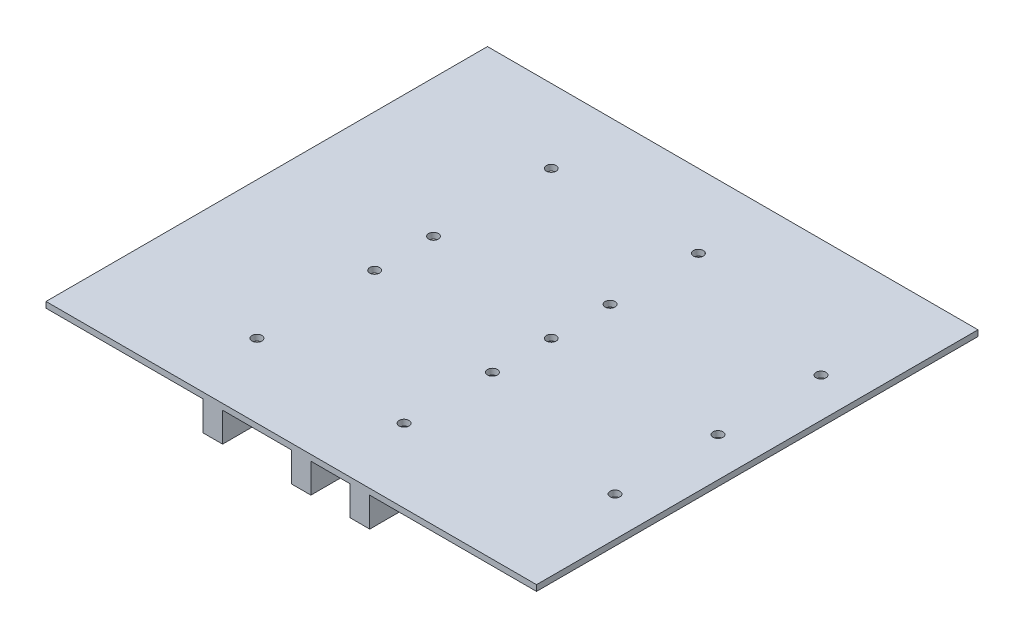
SolidWorks part; units mm, degrees
material "CA"
ref_plane "Front Plane" through (0, 0, 0) normal (0, 0, 1) x (1, 0, 0)
ref_plane "Top Plane" through (0, 0, 0) normal (0, 1, 0) x (1, 0, 0)
ref_plane "Right Plane" through (0, 0, 0) normal (1, 0, 0) x (0, 0, -1)
sketch "Sketch1" plane through (0, 0, 0) normal (0, 1, 0) x (1, 0, 0)
  line L1 (-250, 225) -> (250, 225)
  line L2 (-250, 225) -> (-250, -225)
  line L3 (-250, -225) -> (250, -225)
  line L4 (250, 225) -> (250, -225)
  line L5 (-250, 225) -> (250, -225) construction
  line L6 (-250, -225) -> (250, 225) construction
  point P0 (0, 0)
  dimension "D1" = 450
  dimension "D2" = 500
extrude "Boss-Extrude1" add sketch "Sketch1" along normal blind 6
sketch "Sketch2" plane through (0, 6, 0) normal (0, 1, 0) x (1, 0, 0)
  line L0 (40, 150) -> (40, -150) construction
  line L1 (210, 105) -> (210, -105) construction
  line L2 (0, 0) -> (210, 0) construction
  line L3 (-110, 150) -> (-110, -150) construction
  line L4 (40, 150) -> (-110, 150) construction
  line L5 (40, 0) -> (0, 0) construction
  line L7 (-110, 0) -> (0, 0) construction
  circle A0 centre (210, 105) radius 5
  circle A1 centre (210, -105) radius 5
  circle A2 centre (210, 0) radius 5
  circle A3 centre (40, 150) radius 5
  circle A4 centre (40, 60) radius 5
  circle A5 centre (40, 0) radius 5
  circle A6 centre (-110, 150) radius 5
  circle A7 centre (-110, 30) radius 5
  circle A8 centre (-110, -30) radius 5
  circle A9 centre (40, -60) radius 5
  circle A10 centre (40, -150) radius 5
  circle A11 centre (-110, -150) radius 5
  dimension "D2" = 110
  dimension "D4" = 10
  dimension "D8" = 210
  dimension "D1" = 40
  dimension "D3" = 60
  dimension "D5" = 210
  dimension "D6" = 120
  dimension "D7" = 90
extrude "Cut-Extrude1" cut sketch "Sketch2" against normal up to next
sketch "Sketch3" plane through (0, 0, 0) normal (0, -1, 0) x (1, 0, 0)
  line L0 (10, 225) -> (10, 0) construction
  line L1 (20, 225) -> (0, 225)
  line L2 (20, 225) -> (20, -225)
  line L3 (20, -225) -> (0, -225)
  line L4 (0, 225) -> (0, -225)
  line L5 (-90, 225) -> (-70, 225)
  line L6 (-90, 225) -> (-90, -225)
  line L7 (-90, -225) -> (-70, -225)
  line L8 (-70, 225) -> (-70, -225)
  line L9 (10, 0) -> (20, 0) construction
  line L10 (40, 75.7657) -> (40, -78.1053) construction
  line L11 (0, 0) -> (10, 0) construction
  line L12 (60, -225) -> (80, -225)
  line L13 (60, 225) -> (60, -225)
  line L14 (80, 225) -> (80, -225)
  line L15 (60, 225) -> (80, 225)
  line L16 (0, 225) -> (-70, 225) construction
  line L17 (-70, 225) -> (-62.4977, 224.9543) construction
  line L18 (-80, 225) -> (-80, -225) construction
  dimension "D1" = 60
  dimension "D2" = 20
  dimension "D3" = 10
  dimension "D4" = 450
  dimension "D5" = 20
  dimension "D6" = 450
  dimension "D7" = 80
extrude "Boss-Extrude2" add sketch "Sketch3" along normal blind 30
